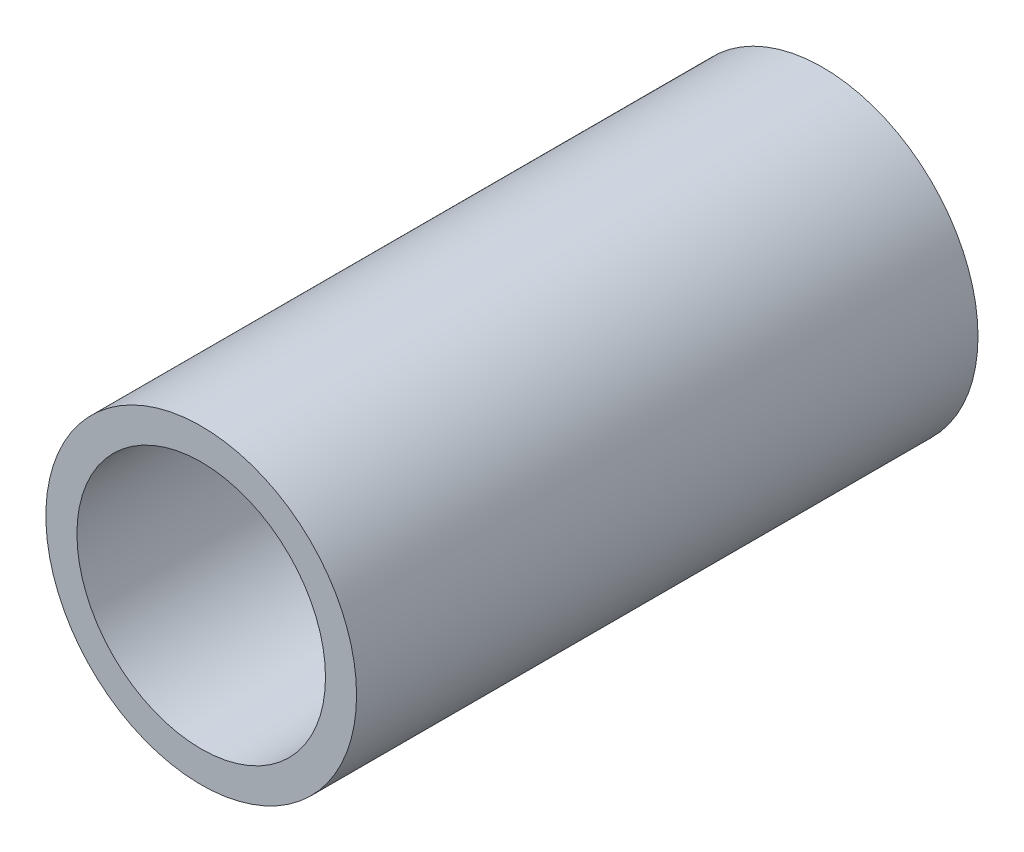
SolidWorks part; units mm, degrees
ref_plane "Piano frontale" through (0, 0, 0) normal (0, 0, 1) x (1, 0, 0)
ref_plane "Piano superiore" through (0, 0, 0) normal (0, 1, 0) x (1, 0, 0)
ref_plane "Piano destro" through (0, 0, 0) normal (1, 0, 0) x (0, 0, -1)
sketch "Schizzo1" plane through (0, 0, 0) normal (0, 0, 1) x (1, 0, 0)
  circle A0 centre (0, 0) radius 5
  dimension "D1" = 10
extrude "Estrusione-Estrusione1" add sketch "Schizzo1" along normal blind 20
sketch "Schizzo2" plane through (0, 0, 20) normal (0, 0, 1) x (1, 0, 0)
  circle A0 centre (0, 0) radius 4
  dimension "D1" = 8
extrude "Taglio-Estrusione1" cut sketch "Schizzo2" against normal blind 18
